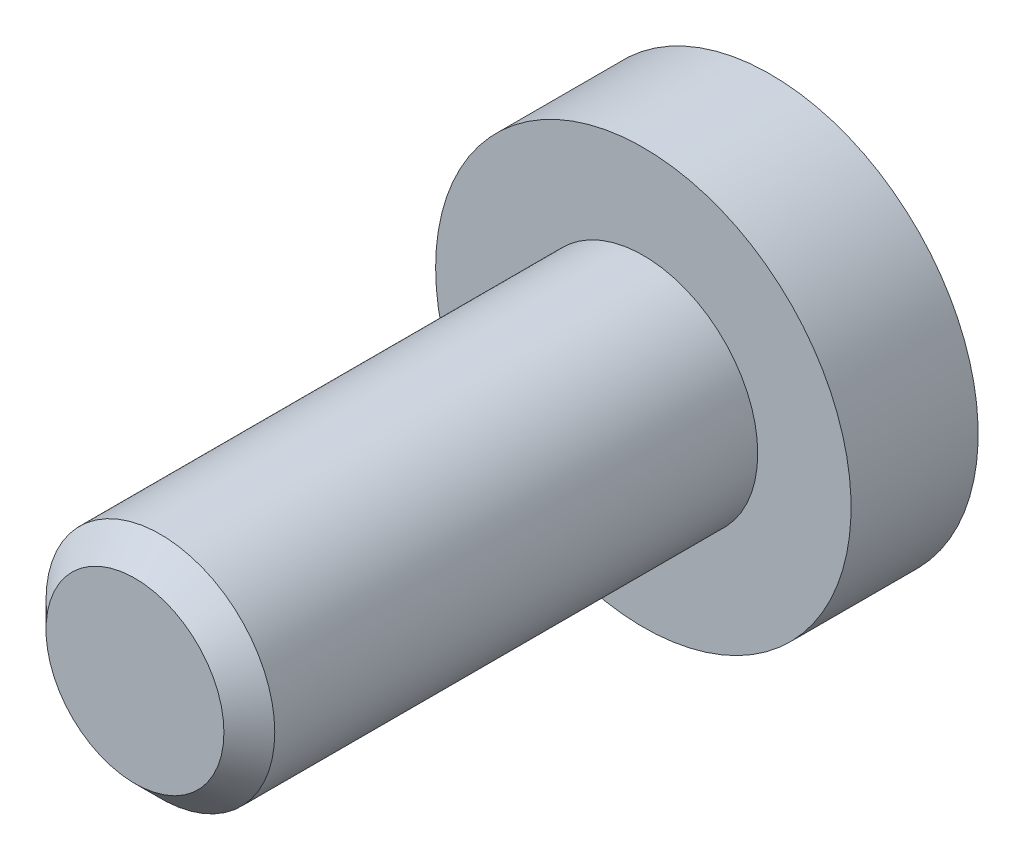
SolidWorks part; units mm, degrees
ref_plane "Front Plane" through (0, 0, 0) normal (0, 0, 1) x (1, 0, 0)
ref_plane "Top Plane" through (0, 0, 0) normal (0, 1, 0) x (1, 0, 0)
ref_plane "Right Plane" through (0, 0, 0) normal (1, 0, 0) x (0, 0, -1)
other "Configuration Table"
sketch "Sketch1" plane through (0, 0, 0) normal (0, 0, 1) x (1, 0, 0)
  circle A0 centre (0, 0) radius 10
  dimension "D1" = 20
extrude "Boss-Extrude1" add sketch "Sketch1" along normal blind 50
sketch "Sketch2" plane through (0, 0, 0) normal (0, 0, -1) x (-1, 0, 0)
  circle A0 centre (0, 0) radius 16.3441
extrude "Boss-Extrude2" add sketch "Sketch2" against normal blind 10
chamfer "Chamfer1" distance 3 angle 45 1 edges at (10, 0, 50)
sketch "Sketch3" plane through (0, 0, 50) normal (0, 0, 1) x (1, 0, 0)
  circle A0 centre (0, 0) radius 9
  dimension "D1" = 18
extrude "Cut-Extrude1" cut sketch "Sketch3" against normal up to surface (40 mm away) flip side to cut up to face at (-16.3441, 0, 10)
